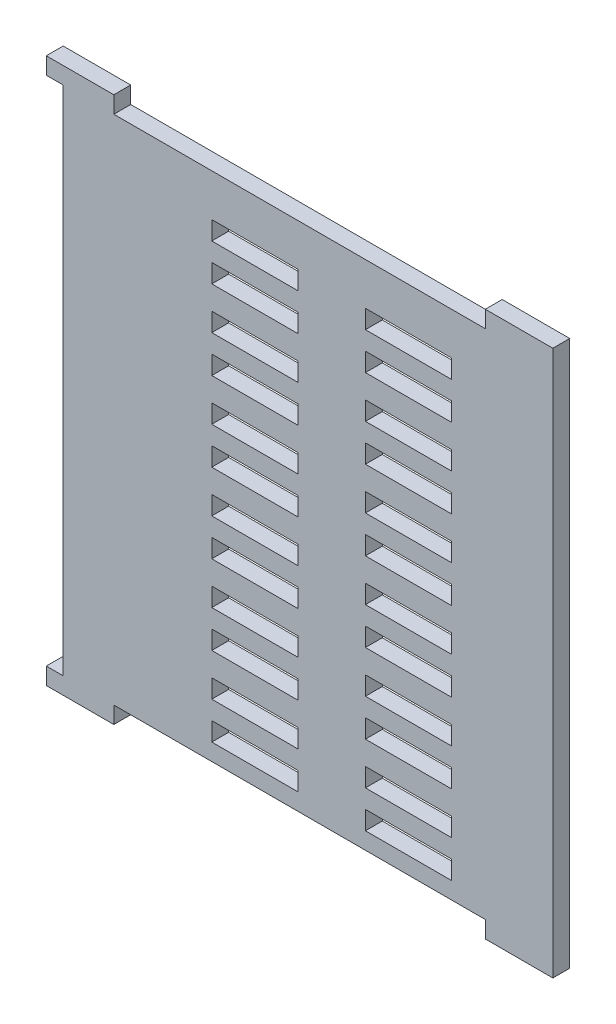
SolidWorks part; units mm, degrees
ref_plane "Front Plane" through (0, 0, 0) normal (0, 0, 1) x (1, 0, 0)
ref_plane "Top Plane" through (0, 0, 0) normal (0, 1, 0) x (1, 0, 0)
ref_plane "Right Plane" through (0, 0, 0) normal (1, 0, 0) x (0, 0, -1)
sketch "Sketch1" plane through (0, 0, 0) normal (0, 0, 1) x (1, 0, 0)
  line L0 (-45.5, 11) -> (-45.5, 16.5)
  line L1 (0, 0) -> (-25.5, 0)
  line L2 (0, 0) -> (0, 5.5)
  line L3 (0, 5.5) -> (-25.5, 5.5)
  line L4 (-25.5, 0) -> (-25.5, 5.5)
  line L5 (-45.5, 0) -> (-71, 0)
  line L6 (-45.5, 0) -> (-45.5, 5.5)
  line L7 (-45.5, 5.5) -> (-71, 5.5)
  line L8 (-71, 0) -> (-71, 5.5)
  line L9 (-45.5, 11) -> (-71, 11)
  line L10 (-71, 11) -> (-71, 16.5)
  line L11 (-45.5, 16.5) -> (-71, 16.5)
  line L12 (0, 11) -> (0, 16.5)
  line L13 (0, 11) -> (-25.5, 11)
  line L14 (-25.5, 11) -> (-25.5, 16.5)
  line L15 (0, 16.5) -> (-25.5, 16.5)
  line L16 (0, 23.5) -> (0, 29)
  line L17 (0, 23.5) -> (-25.5, 23.5)
  line L18 (-25.5, 23.5) -> (-25.5, 29)
  line L19 (0, 29) -> (-25.5, 29)
  line L20 (-45.5, 23.5) -> (-45.5, 29)
  line L21 (-45.5, 23.5) -> (-71, 23.5)
  line L22 (-71, 23.5) -> (-71, 29)
  line L23 (-45.5, 29) -> (-71, 29)
  line L24 (-45.5, 34.5) -> (-45.5, 40)
  line L25 (-45.5, 40) -> (-71, 40)
  line L26 (-71, 34.5) -> (-71, 40)
  line L27 (-45.5, 34.5) -> (-71, 34.5)
  line L28 (0, 34.5) -> (0, 40)
  line L29 (0, 40) -> (-25.5, 40)
  line L30 (-25.5, 34.5) -> (-25.5, 40)
  line L31 (0, 34.5) -> (-25.5, 34.5)
  line L32 (0, 47) -> (0, 52.5)
  line L33 (0, 47) -> (-25.5, 47)
  line L34 (-25.5, 47) -> (-25.5, 52.5)
  line L35 (0, 52.5) -> (-25.5, 52.5)
  line L36 (-45.5, 47) -> (-45.5, 52.5)
  line L37 (-45.5, 47) -> (-71, 47)
  line L38 (-71, 47) -> (-71, 52.5)
  line L39 (-45.5, 52.5) -> (-71, 52.5)
  line L40 (-45.5, 58) -> (-45.5, 63.5)
  line L41 (-45.5, 63.5) -> (-71, 63.5)
  line L42 (-71, 58) -> (-71, 63.5)
  line L43 (-45.5, 58) -> (-71, 58)
  line L44 (0, 58) -> (0, 63.5)
  line L45 (0, 63.5) -> (-25.5, 63.5)
  line L46 (-25.5, 58) -> (-25.5, 63.5)
  line L47 (0, 58) -> (-25.5, 58)
  line L48 (0, 70.5) -> (0, 76)
  line L49 (0, 70.5) -> (-25.5, 70.5)
  line L50 (-25.5, 70.5) -> (-25.5, 76)
  line L51 (0, 76) -> (-25.5, 76)
  line L52 (-45.5, 70.5) -> (-45.5, 76)
  line L53 (-45.5, 70.5) -> (-71, 70.5)
  line L54 (-71, 70.5) -> (-71, 76)
  line L55 (-45.5, 76) -> (-71, 76)
  line L56 (-45.5, 81.5) -> (-45.5, 87)
  line L57 (-45.5, 87) -> (-71, 87)
  line L58 (-71, 81.5) -> (-71, 87)
  line L59 (-45.5, 81.5) -> (-71, 81.5)
  line L60 (0, 81.5) -> (0, 87)
  line L61 (0, 87) -> (-25.5, 87)
  line L62 (-25.5, 81.5) -> (-25.5, 87)
  line L63 (0, 81.5) -> (-25.5, 81.5)
  line L64 (0, 94) -> (0, 99.5)
  line L65 (0, 94) -> (-25.5, 94)
  line L66 (-25.5, 94) -> (-25.5, 99.5)
  line L67 (0, 99.5) -> (-25.5, 99.5)
  line L68 (-45.5, 94) -> (-45.5, 99.5)
  line L69 (-45.5, 94) -> (-71, 94)
  line L70 (-71, 94) -> (-71, 99.5)
  line L71 (-45.5, 99.5) -> (-71, 99.5)
  line L72 (-45.5, 105) -> (-45.5, 110.5)
  line L73 (-45.5, 110.5) -> (-71, 110.5)
  line L74 (-71, 105) -> (-71, 110.5)
  line L75 (-45.5, 105) -> (-71, 105)
  line L76 (0, 105) -> (0, 110.5)
  line L77 (0, 110.5) -> (-25.5, 110.5)
  line L78 (-25.5, 105) -> (-25.5, 110.5)
  line L79 (0, 105) -> (-25.5, 105)
  line L80 (0, 117.5) -> (0, 123)
  line L81 (0, 117.5) -> (-25.5, 117.5)
  line L82 (-25.5, 117.5) -> (-25.5, 123)
  line L83 (0, 123) -> (-25.5, 123)
  line L84 (-45.5, 117.5) -> (-45.5, 123)
  line L85 (-45.5, 117.5) -> (-71, 117.5)
  line L86 (-71, 117.5) -> (-71, 123)
  line L87 (-45.5, 123) -> (-71, 123)
  line L88 (-45.5, 128.5) -> (-45.5, 134)
  line L89 (-45.5, 134) -> (-71, 134)
  line L90 (-71, 128.5) -> (-71, 134)
  line L91 (-45.5, 128.5) -> (-71, 128.5)
  line L92 (0, 128.5) -> (0, 134)
  line L93 (0, 134) -> (-25.5, 134)
  line L94 (-25.5, 128.5) -> (-25.5, 134)
  line L95 (0, 128.5) -> (-25.5, 128.5)
  line L96 (-100, 151.5) -> (-100, 146.5)
  line L97 (-120, 151.5) -> (-100, 151.5)
  line L98 (-120, 151.5) -> (-120, 146.5)
  line L99 (-120, -10) -> (-100, -10)
  line L100 (30, 151.5) -> (30, -10)
  line L101 (-100, 146.5) -> (10, 146.5)
  line L102 (10, 146.5) -> (10, 151.5)
  line L103 (-150, 70.75) -> (30, 70.75) construction
  line L104 (10, -5) -> (10, -10)
  line L105 (-100, -5) -> (10, -5)
  line L106 (-100, -10) -> (-100, -5)
  line L107 (10, 151.5) -> (30, 151.5)
  line L108 (10, -10) -> (30, -10)
  line L109 (-120, 146.5) -> (-115, 146.5)
  line L110 (-115, 146.5) -> (-115, -5)
  line L111 (-115, -5) -> (-120, -5)
  line L112 (-120, -5) -> (-120, -10)
  point P113 (-117.5, -5)
  point P116 (-115, -5)
  point P117 (-115, -5)
  dimension "D1" = 25.5
  dimension "D2" = 25.5
  dimension "D3" = 20
  dimension "D4" = 5.5
  dimension "D5" = 5.5
  dimension "D7" = 11
  dimension "D9" = 150
  dimension "D10" = 30
  dimension "D11" = 10
  dimension "D12" = 23
  dimension "D13" = 128.5
  dimension "D14" = 5
  dimension "D15" = 20
  dimension "D16" = 20
  dimension "D17" = 5
  dimension "D18" = 5
  dimension "D19" = 151.5
  dimension "D20" = 110
  dimension "D6" = 2
  dimension "D8" = 6
extrude "Boss-Extrude1" add sketch "Sketch1" along normal blind 5
